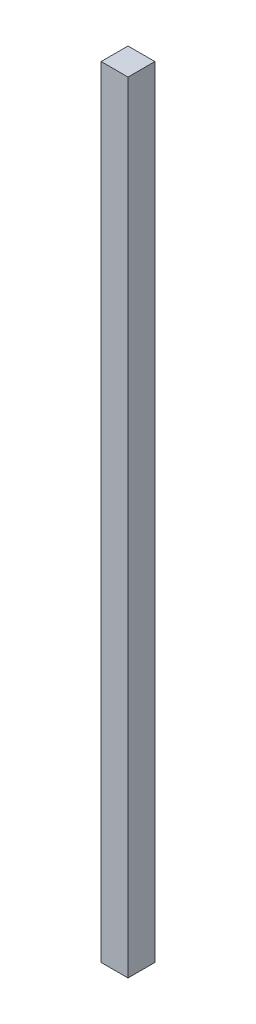
SolidWorks part; units mm, degrees
ref_plane "Front Plane" through (0, 0, 0) normal (0, 0, 1) x (1, 0, 0)
ref_plane "Top Plane" through (0, 0, 0) normal (0, 1, 0) x (1, 0, 0)
ref_plane "Right Plane" through (0, 0, 0) normal (1, 0, 0) x (0, 0, -1)
sketch "Sketch1" plane through (0, 0, 0) normal (0, 0, 1) x (1, 0, 0)
  line L0 (0, 0) -> (10, 0)
  line L1 (10, 0) -> (10, -290)
  line L2 (10, -290) -> (0, -290)
  line L3 (0, -290) -> (0, 0)
  dimension "D1" = 290
  dimension "D2" = 10
extrude "Boss-Extrude1" add sketch "Sketch1" along normal blind 10
